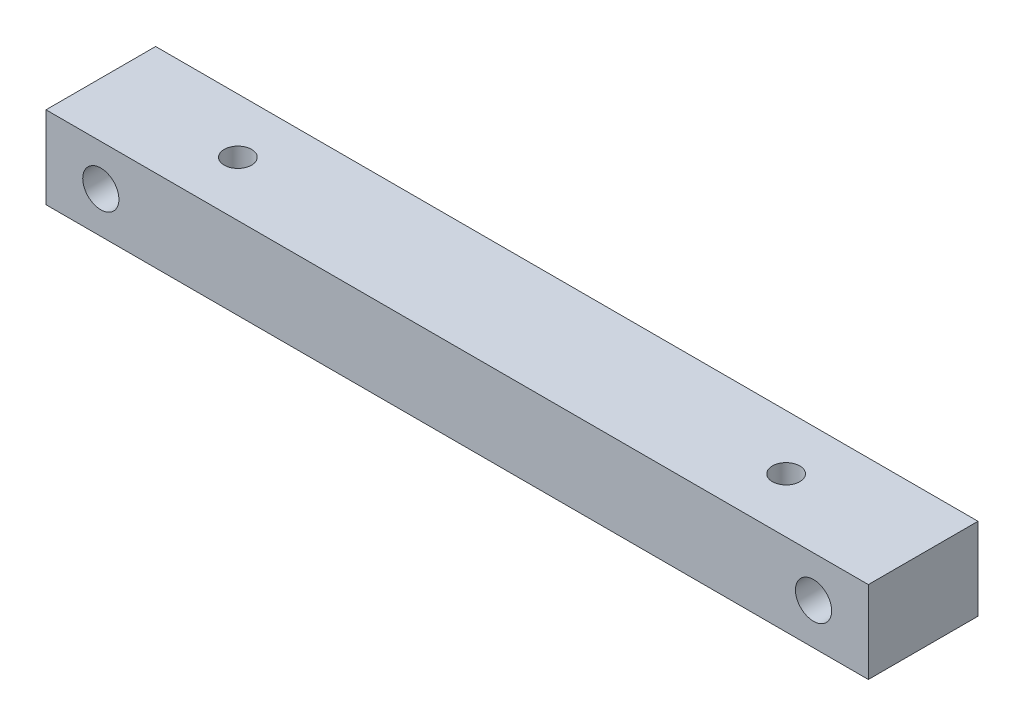
SolidWorks part; units mm, degrees
ref_plane "前基準面" through (0, 0, 0) normal (0, 0, 1) x (1, 0, 0)
ref_plane "上基準面" through (0, 0, 0) normal (0, 1, 0) x (1, 0, 0)
ref_plane "右基準面" through (0, 0, 0) normal (1, 0, 0) x (0, 0, -1)
sketch "草圖1" plane through (0, 0, 0) normal (0, 0, 1) x (1, 0, 0)
  line L0 (75, 7.5) -> (-75, -7.5) construction
  line L1 (-75, 7.5) -> (75, 7.5)
  line L2 (-75, 7.5) -> (-75, -7.5)
  line L3 (-75, -7.5) -> (75, -7.5)
  line L4 (75, 7.5) -> (75, -7.5)
  dimension "D1" = 150
  dimension "D2" = 15
extrude "伸長1" add sketch "草圖1" along normal blind 20
hole_wizard "M6 螺紋孔1" positions "草圖3" profile "草圖2" tap size "M6" standard "GB" end condition through all
sketch "草圖3" plane through (0, 7.5, 0) normal (0, 1, 0) x (-1, 0, 0)
  line L4 (0, 0) -> (0, 10) construction
  point P0 (50, 10)
  point P19 (-50, 10)
  dimension "D1" = 10
  dimension "D2" = 50
sketch "草圖2" plane through (-50, 7.5, 10) normal (1, 0, 0) x (0, 0, 1)
  line L0 (0, 0) -> (0, 15)
  line L1 (0, 15) -> (2.5, 15)
  line L2 (2.5, 15) -> (2.5, 0)
  line L5 (2.5, 0) -> (0, 0)
  line L11 (0, -6.35) -> (0, 107.95) construction
  dimension "貫穿螺孔鑽直徑" = 5
  dimension "貫穿螺孔鑽深度" = 15
cosmetic thread "鑽孔螺紋1"
cosmetic thread "鑽孔螺紋2"
hole_wizard "M6 六角承窩頭蓋螺釘的柱孔1" positions "草圖6" profile "草圖7" counterbore size "M6" standard "ISO" end condition through all
sketch "草圖6" plane through (0, 0, 0) normal (0, 0, -1) x (-1, 0, 0)
  point P0 (65, 0)
  point P1 (-65, 0)
  dimension "D1" = 65
  dimension "D2" = 65
sketch "草圖7" plane through (-65, 0, 0) normal (1, 0, 0) x (0, 1, 0)
  line L0 (0, 0) -> (0, 20)
  line L1 (0, 20) -> (3.3, 20)
  line L3 (3.3, 20) -> (3.3, 6)
  line L4 (3.3, 6) -> (5.5, 6)
  line L5 (5.5, 6) -> (5.5, 0)
  line L7 (5.5, 0) -> (0, 0)
  line L11 (0, -6.35) -> (0, 107.95) construction
  dimension "貫穿孔直徑" = 6.6
  dimension "貫穿孔深度" = 20
  dimension "柱孔直徑" = 11
  dimension "柱孔深度" = 6
